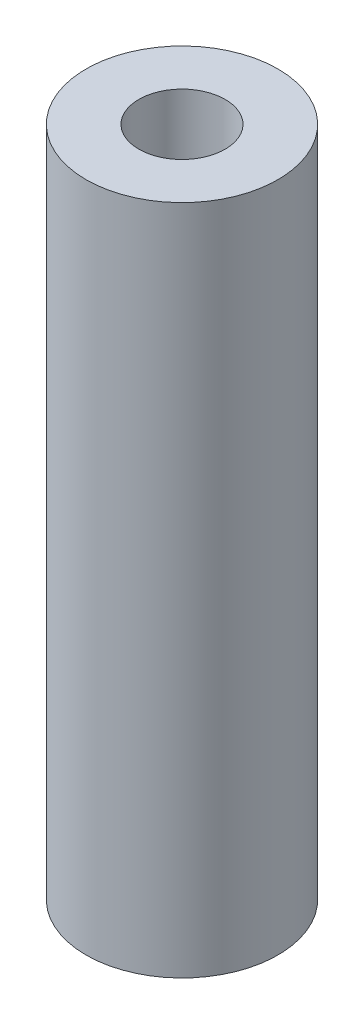
SolidWorks part; units mm, degrees
material "6061-T6 (SS)"
ref_plane "Alzado" through (0, 0, 0) normal (0, 0, 1) x (1, 0, 0)
ref_plane "Planta" through (0, 0, 0) normal (0, 1, 0) x (1, 0, 0)
ref_plane "Vista lateral" through (0, 0, 0) normal (1, 0, 0) x (0, 0, -1)
sketch "Croquis1" plane through (0, 0, 0) normal (0, 1, 0) x (1, 0, 0)
  circle A0 centre (0, 0) radius 5
  dimension "D1" = 10
extrude "Saliente-Extruir1" add sketch "Croquis1" along normal mid plane 35
hole_wizard "Taladro de margen para M41" positions "Croquis2" profile "Croquis3" hole size "M4" standard "Ansi Metric" end condition through all
sketch "Croquis2" plane through (0, 17.5, 0) normal (0, 1, 0) x (1, 0, 0)
  point P0 (0, 0)
sketch "Croquis3" plane through (0, 17.5, 0) normal (1, 0, 0) x (0, 0, 1)
  line L0 (0, 0) -> (0, 35)
  line L1 (0, 35) -> (2.25, 35)
  line L2 (2.25, 35) -> (2.25, 0)
  line L5 (2.25, 0) -> (0, 0)
  line L11 (0, -6.35) -> (0, 107.95) construction
  dimension "Diámetro de taladro hasta el siguiente" = 4.5
  dimension "Profundidad de taladro hasta el siguiente" = 35
